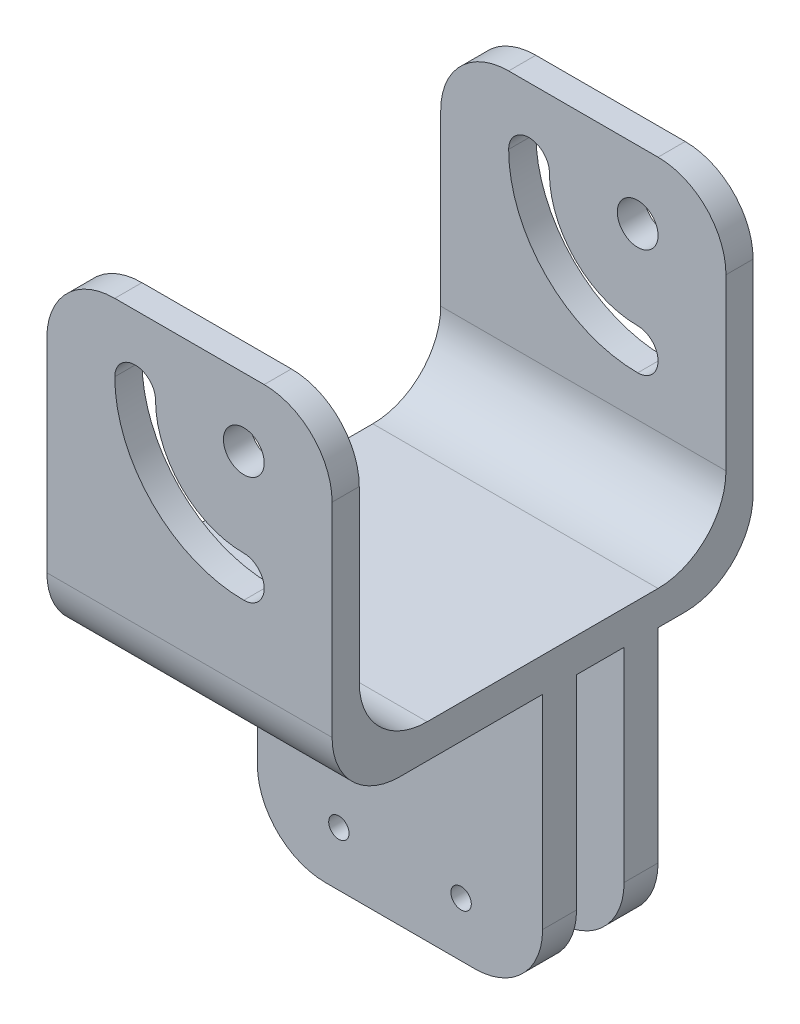
SolidWorks part; units mm, degrees
other "Marcação1"
sketch "Esboço5" plane through (0, 50, 68.25) normal (-0.797, 0.1637, 0.5813) x (0.5636, -0.1442, 0.8134)
material "Nylon - impressão"
ref_plane "Plano frontal" through (0, 0, 0) normal (0, 0, 1) x (1, 0, 0)
ref_plane "Plano superior" through (0, 0, 0) normal (0, 1, 0) x (1, 0, 0)
ref_plane "Plano direito" through (0, 0, 0) normal (1, 0, 0) x (0, 0, -1)
sketch "Esboço1" plane through (0, 0, 0) normal (0, 0, 1) x (1, 0, 0)
  line L0 (0, 0) -> (0, 50)
  line L1 (0, 50) -> (42, 50)
  line L2 (42, 50) -> (42, 0)
  line L3 (42, 0) -> (0, 0)
  line L4 (29, 40) -> (29, 37) construction
  circle A0 centre (29, 40) radius 3
  arc A2 (29, 24) -> (13, 40) centre (29, 40) cw construction
  arc A3 (10, 40) -> (29, 21) centre (29, 40) ccw
  arc A4 (16, 40) -> (29, 27) centre (29, 40) ccw
  arc A5 (16, 40) -> (10, 40) centre (13, 40) ccw
  arc A6 (29, 21) -> (29, 27) centre (29, 24) ccw
  point P10 (17.6863, 28.6863)
  dimension "D3" = 6
  dimension "D5" = 16
  dimension "D6" = 13
  dimension "D1" = 29
  dimension "D2" = 50
  dimension "D4" = 13
extrude "Ressalto-extrusão2" add sketch "Esboço1" along normal blind 62
sketch "Esboço3" plane through (0, 50, 0) normal (0, 1, 0) x (1, 0, 0)
  line L0 (0, -58) -> (42, -58)
  line L1 (0, -62) -> (0, 0) construction
  line L2 (42, -62) -> (42, 0) construction
  line L3 (42, -58) -> (42, -4)
  line L4 (42, -4) -> (0, -4)
  line L5 (0, -4) -> (0, -58)
  line L6 (42, 0) -> (0, 0) construction
  dimension "D1" = 4
  dimension "D2" = 4
extrude "Corte-extrusão1" cut sketch "Esboço3" against normal blind 45
sketch "Esboço7" plane through (0, 0, 0) normal (0, -1, 0) x (1, 0, 0)
  line L0 (0, 14) -> (42, 14)
  line L1 (0, 62) -> (0, 0) construction
  line L2 (42, 62) -> (42, 0) construction
  line L3 (42, 14) -> (42, 19)
  line L4 (42, 19) -> (0, 19)
  line L5 (0, 19) -> (0, 14)
  line L6 (0, 26) -> (42, 26)
  line L7 (42, 26) -> (42, 31)
  line L8 (42, 31) -> (0, 31)
  line L9 (0, 31) -> (0, 26)
  dimension "D1" = 5
  dimension "D2" = 5
  dimension "D3" = 7
extrude "Ressalto-extrusão3" add sketch "Esboço7" along normal blind 40
sketch "Esboço10" plane through (0, 0, 14) normal (0, 0, -1) x (-1, 0, 0)
  line L0 (-42, -40) -> (-42, 0) construction
  line L1 (0, -40) -> (0, 0) construction
  line L2 (0, -40) -> (-42, -40) construction
  circle A5 centre (-30, -32) radius 1.5
  circle A6 centre (-12, -32) radius 1.5
  dimension "D7" = 3
  dimension "D8" = 3
  dimension "D2" = 12
  dimension "D3" = 12
  dimension "D10" = 18
  dimension "D11" = 8
extrude "Corte-extrusão2" cut sketch "Esboço10" against normal through all
fillet "Filete1" radius 10 12 edges at (21, 5, 4) (0, 50, 2) (42, 50, 2) (21, 5, 58) (21, 0, 62) (21, 0, 0) (42, -40, 28.5) (42, -40, 16.5) (0, -40, 16.5) (0, -40, 28.5) (0, 50, 60) (42, 50, 60)
